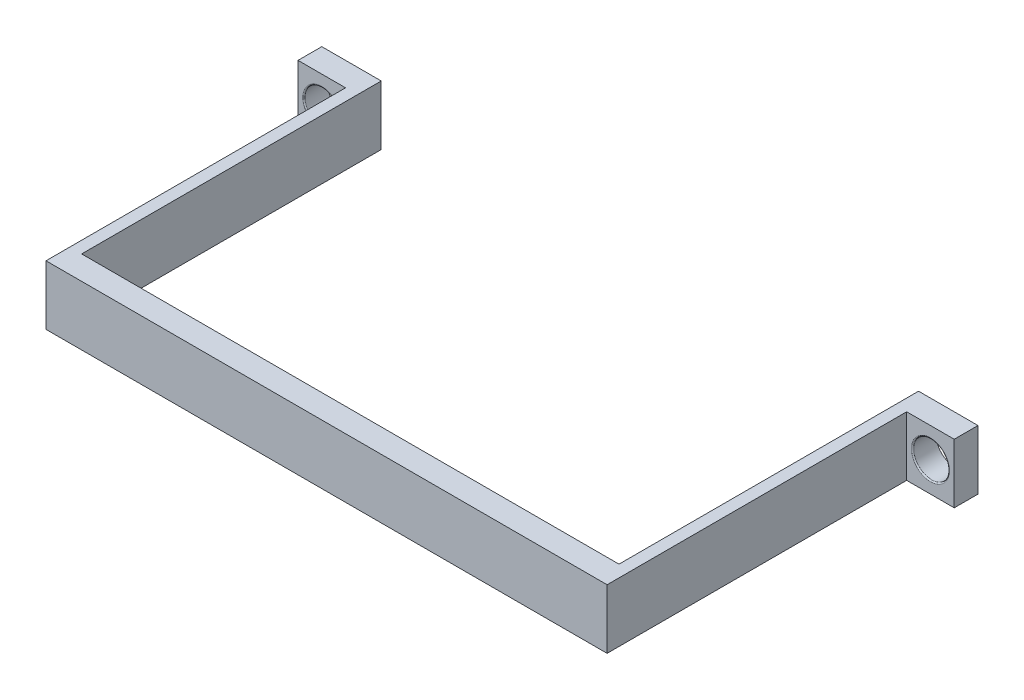
SolidWorks part; units mm, degrees
ref_plane "Front Plane" through (0, 0, 0) normal (0, 0, 1) x (1, 0, 0)
ref_plane "Top Plane" through (0, 0, 0) normal (0, 1, 0) x (1, 0, 0)
ref_plane "Right Plane" through (0, 0, 0) normal (1, 0, 0) x (0, 0, -1)
sketch "Sketch10" plane through (0, 0, 0) normal (0, 0, 1) x (1, 0, 0)
  line L1 (-38.4102, -70.0764) -> (11.7898, -70.0764)
  line L2 (-38.4102, -70.0764) -> (-38.4102, -75.0764)
  line L3 (-38.4102, -75.0764) -> (11.7898, -75.0764)
  line L4 (11.7898, -70.0764) -> (11.7898, -75.0764)
  dimension "D1" = 50.2
  dimension "D2" = 5
extrude "Boss-Extrude5" add sketch "Sketch10" along normal blind 27.2 contours L1 L4 L3 L2
sketch "Sketch15" plane through (0, -75.0764, 0) normal (0, -1, 0) x (-1, 0, 0)
  line L0 (-2.75, 0) -> (2.75, 0) construction
  line L1 (35.9102, 0) -> (-9.2898, 0)
  line L2 (35.9102, 0) -> (35.9102, -25.2)
  line L3 (35.9102, -25.2) -> (-9.2898, -25.2)
  line L4 (-9.2898, 0) -> (-9.2898, -25.2)
  line L5 (-11.7898, -27.2) -> (-11.7898, 0) construction
  dimension "D1" = 45.2
  dimension "D2" = 25.2
  dimension "D3" = 2.5
extrude "Cut-Extrude7" cut sketch "Sketch15" against normal through all
sketch "Sketch16" plane through (0, 0, 27.2) normal (0, 0, 1) x (1, 0, 0)
  line L0 (-38.4102, -75.0764) -> (11.7898, -75.0764) construction
  line L1 (-38.4102, -70.0764) -> (-36.9102, -70.0764)
  line L2 (-38.4102, -70.0764) -> (-38.4102, -75.0764)
  line L3 (-38.4102, -75.0764) -> (-36.9102, -75.0764)
  line L4 (-36.9102, -70.0764) -> (-36.9102, -75.0764)
  dimension "D1" = 1.5
extrude "Cut-Extrude8" cut sketch "Sketch16" against normal blind 25.2
sketch "Sketch17" plane through (0, 0, 27.2) normal (0, 0, 1) x (1, 0, 0)
  line L0 (-36.9102, -75.0764) -> (11.7898, -75.0764) construction
  line L1 (11.7898, -70.0764) -> (10.2898, -70.0764)
  line L2 (11.7898, -70.0764) -> (11.7898, -75.0764)
  line L3 (11.7898, -75.0764) -> (10.2898, -75.0764)
  line L4 (10.2898, -70.0764) -> (10.2898, -75.0764)
  dimension "D1" = 1.5
extrude "Cut-Extrude9" cut sketch "Sketch17" against normal blind 25.2
sketch "Sketch19" plane through (-38.4102, 0, 0) normal (-1, 0, 0) x (0, 0, 1)
  line L1 (0, -70.0764) -> (2, -70.0764)
  line L2 (0, -70.0764) -> (0, -75.0764)
  line L3 (0, -75.0764) -> (2, -75.0764)
  line L4 (2, -70.0764) -> (2, -75.0764)
extrude "Boss-Extrude6" add sketch "Sketch19" along normal blind 2.5
sketch "Sketch20" plane through (11.7898, 0, 0) normal (1, 0, 0) x (0, 0, -1)
  line L0 (0, 2.75) -> (0, -2.75) construction
  line L1 (-2, -70.0764) -> (0, -70.0764)
  line L2 (-2, -70.0764) -> (-2, -75.0764)
  line L3 (-2, -75.0764) -> (0, -75.0764)
  line L4 (0, -70.0764) -> (0, -75.0764)
  line L5 (-2, -75.0764) -> (0, -75.0764) construction
extrude "Boss-Extrude7" add sketch "Sketch20" along normal blind 2.5
sketch "Sketch21" plane through (0, 0, 2) normal (0, 0, 1) x (1, 0, 0)
  line L0 (-40.9102, -72.5764) -> (15.8447, -72.5764) construction
  line L1 (-40.9102, -75.0764) -> (-40.9102, -70.0764) construction
  line L2 (-38.9102, -70.0764) -> (-38.9102, -77.219) construction
  line L3 (-36.9102, -70.0764) -> (-40.9102, -70.0764) construction
  line L4 (12.2898, -70.0764) -> (12.2898, -80.1842) construction
  line L5 (14.2898, -70.0764) -> (10.2898, -70.0764) construction
  circle A0 centre (-38.9102, -72.5764) radius 1.5
  dimension "D1" = 3
extrude "Cut-Extrude10" cut sketch "Sketch21" against normal blind 2.5
fillet "Fillet4" radius 0.1 1 edges at (-37.4102, -72.5764, 2)
sketch "Sketch22" plane through (0, 0, 2) normal (0, 0, 1) x (1, 0, 0)
  line L0 (12.2898, -70.0764) -> (12.2898, -76.2185) construction
  line L1 (14.2898, -70.0764) -> (10.2898, -70.0764) construction
  line L2 (14.2898, -72.5764) -> (9.1793, -72.5764) construction
  line L3 (14.2898, -70.0764) -> (14.2898, -75.0764) construction
  circle A0 centre (12.2898, -72.5764) radius 1.5
  dimension "D1" = 3
extrude "Cut-Extrude11" cut sketch "Sketch22" against normal blind 2.5
fillet "Fillet5" radius 0.1 1 edges at (13.7898, -72.5764, 2)
